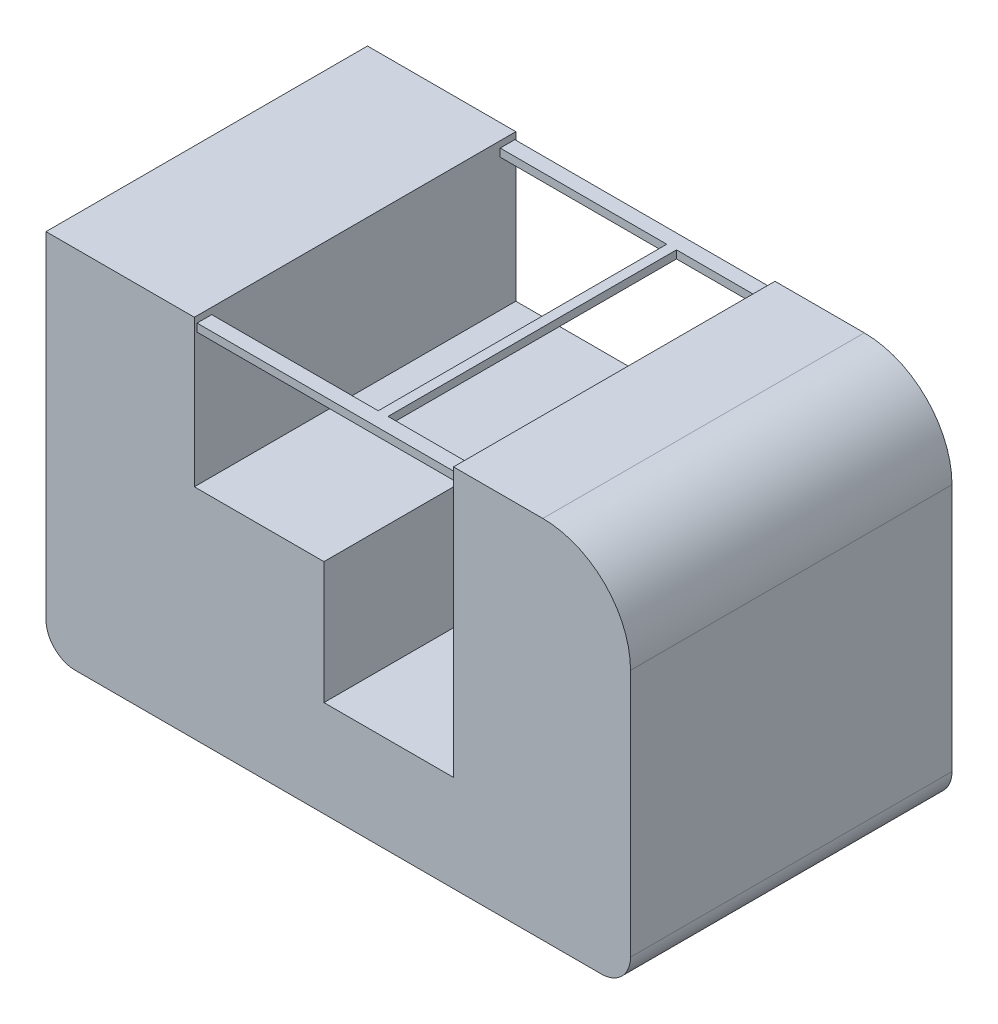
SolidWorks part; units mm, degrees
ref_plane "Front Plane" through (0, 0, 0) normal (0, 0, 1) x (1, 0, 0)
ref_plane "Top Plane" through (0, 0, 0) normal (0, 1, 0) x (1, 0, 0)
ref_plane "Right Plane" through (0, 0, 0) normal (1, 0, 0) x (0, 0, -1)
sketch "Sketch2" plane through (0, 0, 0) normal (0, 0, 1) x (1, 0, 0)
  line L1 (0, 0) -> (50.8, 0)
  line L2 (0, 0) -> (0, 31.75)
  line L3 (0, 31.75) -> (50.8, 31.75)
  line L4 (50.8, 0) -> (50.8, 31.75)
  dimension "D1" = 50.8
  dimension "D2" = 31.75
extrude "Boss-Extrude1" add sketch "Sketch2" along normal blind 27.94
sketch "Sketch3" plane through (0, 0, 27.94) normal (0, 0, 1) x (1, 0, 0)
  line L0 (24.1548, 18.988) -> (24.1548, 8.3768)
  line L2 (50.8, 31.75) -> (0, 31.75) construction
  line L3 (12.8939, 31.75) -> (12.8939, 18.988)
  line L4 (12.8939, 18.988) -> (24.1548, 18.988)
  line L5 (35.4157, 18.988) -> (35.4157, 31.75)
  line L6 (35.4157, 31.75) -> (12.8939, 31.75)
  line L7 (24.1548, 8.3768) -> (35.4157, 8.3768)
  line L8 (35.4157, 8.3768) -> (35.4157, 18.988)
extrude "Cut-Extrude2" cut sketch "Sketch3" against normal blind 27.94
fillet "Fillet1" radius 7.62 1 edges at (50.8, 31.75, 13.97)
sketch "Sketch4" plane through (0, 0, 27.94) normal (0, 0, 1) x (1, 0, 0)
  line L0 (35.4157, 31.75) -> (27.7958, 31.75)
sketch "Sketch5" plane through (35.4157, 0, 0) normal (-1, 0, 0) x (0, 0, 1)
  line L3 (0.0892, 31.1947) -> (1.3592, 31.1947)
  line L4 (0.0892, 31.1947) -> (0.0892, 30.5092)
  line L5 (0.0892, 30.5092) -> (1.3592, 30.5092)
  line L6 (1.3592, 31.1947) -> (1.3592, 30.5092)
  line L7 (0.0892, 31.1947) -> (1.3592, 30.5092) construction
  line L8 (0.0892, 30.5092) -> (1.3592, 31.1947) construction
  line L9 (26.4331, 31.1947) -> (27.7031, 31.1947)
  line L10 (26.4331, 31.1947) -> (26.4331, 30.5092)
  line L11 (26.4331, 30.5092) -> (27.7031, 30.5092)
  line L12 (27.7031, 31.1947) -> (27.7031, 30.5092)
  line L13 (26.4331, 31.1947) -> (27.7031, 30.5092) construction
  line L14 (26.4331, 30.5092) -> (27.7031, 31.1947) construction
  dimension "D1" = 1.27
  dimension "D2" = 1.27
  dimension "D3" = 0.6855
  dimension "D4" = 0.6855
extrude "Boss-Extrude2" add sketch "Sketch5" along normal blind 27.94
sketch "Sketch6" plane through (0, 0, 1.3592) normal (0, 0, 1) x (1, 0, 0)
  line L0 (27.3678, 31.1947) -> (27.3678, 30.5092)
  line L1 (12.8939, 31.1947) -> (35.4157, 31.1947) construction
  line L2 (12.8939, 30.5092) -> (35.4157, 30.5092) construction
  line L3 (27.3678, 30.5092) -> (28.217, 30.5092)
  line L4 (28.217, 30.5092) -> (28.217, 31.1947)
  line L5 (28.217, 31.1947) -> (27.3678, 31.1947)
extrude "Boss-Extrude3" add sketch "Sketch6" along normal blind 25.4
fillet "Fillet2" radius 2.54 1 edges at (50.8, 0, 13.97)
fillet "Fillet3" radius 2.54 1 edges at (0, 0, 13.97)
